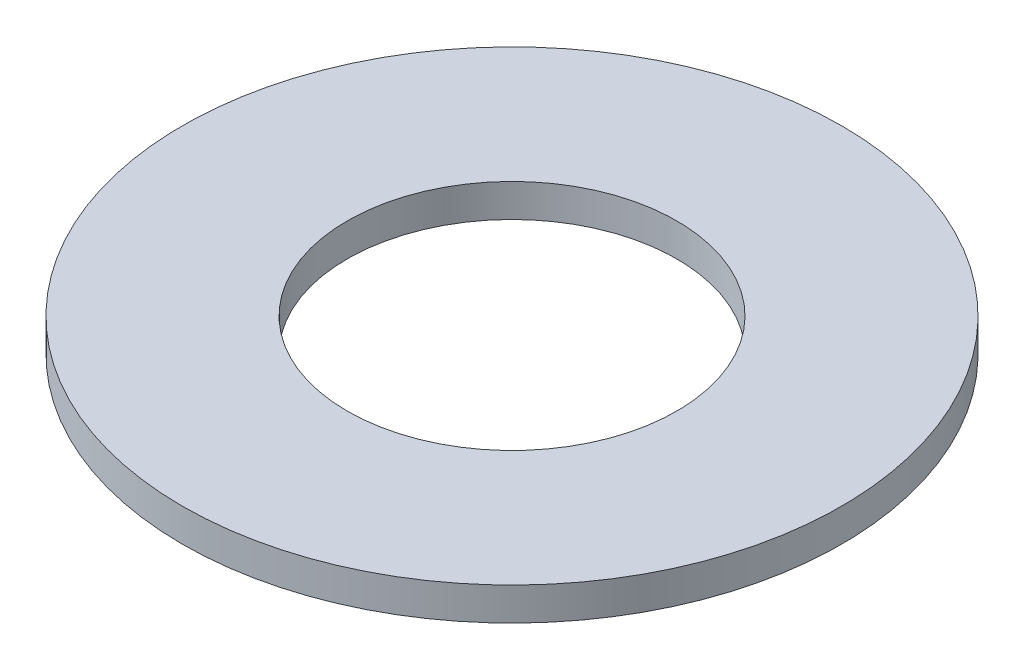
SolidWorks part; units mm, degrees
ref_plane "Front Plane" through (0, 0, 0) normal (0, 0, 1) x (1, 0, 0)
ref_plane "Top Plane" through (0, 0, 0) normal (0, 1, 0) x (1, 0, 0)
ref_plane "Right Plane" through (0, 0, 0) normal (1, 0, 0) x (0, 0, -1)
sketch "Sketch1" plane through (0, 0, 0) normal (0, 1, 0) x (1, 0, 0)
  circle A0 centre (0, 0) radius 2.5
  circle A1 centre (0, 0) radius 5
  dimension "D1" = 5
  dimension "D2" = 10
extrude "Boss-Extrude1" add sketch "Sketch1" along normal blind 0.5
